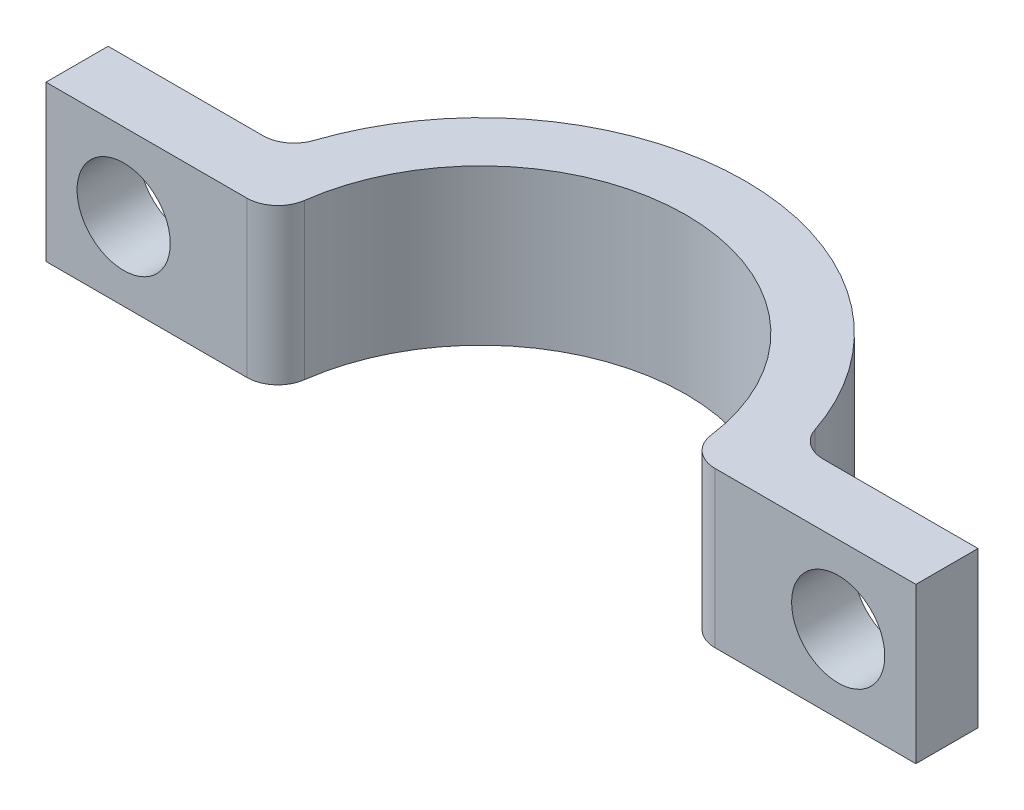
SolidWorks part; units mm, degrees
ref_plane "Front Plane" through (0, 0, 0) normal (0, 0, 1) x (1, 0, 0)
ref_plane "Top Plane" through (0, 0, 0) normal (0, 1, 0) x (1, 0, 0)
ref_plane "Right Plane" through (0, 0, 0) normal (1, 0, 0) x (0, 0, -1)
sketch "Sketch1" plane through (0, 0, 0) normal (0, 1, 0) x (1, 0, 0)
  line L0 (0, 10.5419) -> (0, -11.3726) construction
  line L1 (-8.5, 0) -> (-14, 0)
  line L2 (-14, 0) -> (-14, 2)
  line L3 (-14, 2) -> (-8.2614, 2)
  line L4 (-8.5, 0) -> (-6.6, 0)
  line L5 (0, 8.5) -> (0, 6.5)
  line L6 (8.5, 0) -> (6.6, 0)
  line L7 (14, 2) -> (8.2614, 2)
  line L8 (14, 0) -> (14, 2)
  line L9 (8.5, 0) -> (14, 0)
  arc A0 (6.6, 0) -> (-6.6, 0) centre (0, 0) ccw
  arc A1 (8.2614, 2) -> (-8.2614, 2) centre (0, 0) ccw
  dimension "D1" = 13.2
  dimension "D2" = 17
  dimension "D3" = 2
  dimension "D4" = 14
extrude "Boss-Extrude1" add sketch "Sketch1" along normal blind 5 contours L5 A1 L3 L2 L1 L4 A0 | L7 A1 L5 A0 L6 L9 L8
sketch "Sketch2" plane through (0, 0, -2) normal (0, 0, -1) x (-1, 0, 0)
  line L0 (-11.5, 0) -> (-11.5, 5) construction
  line L3 (0, 5) -> (0, 0) construction
  line L4 (8.2614, 5) -> (-8.2614, 5) construction
  line L5 (-8.2614, 0) -> (8.2614, 0) construction
  line L6 (-14, 0) -> (-8.2614, 0) construction
  line L7 (-14, 5) -> (-8.2614, 5) construction
  line L8 (-14, 5) -> (-14, 0) construction
  circle A0 centre (-11.5, 2.5) radius 1.5
  circle A1 centre (11.5, 2.5) radius 1.5
  dimension "D1" = 2.5
  dimension "D2" = 3
extrude "Cut-Extrude1" cut sketch "Sketch2" against normal through all
fillet "Fillet1" radius 1 4 edges at (-8.2614, 2.5, -2) (6.6, 2.5, 0) (-6.6, 2.5, 0) (8.2614, 2.5, -2)
